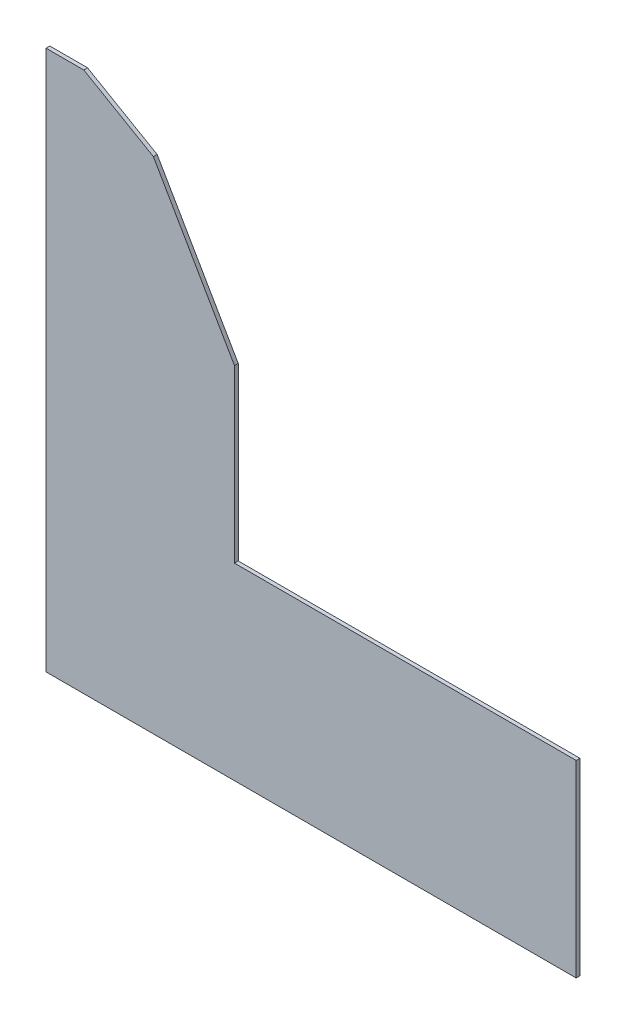
SolidWorks part; units mm, degrees
ref_plane "Front Plane" through (0, 0, 0) normal (0, 0, 1) x (1, 0, 0)
ref_plane "Top Plane" through (0, 0, 0) normal (0, 1, 0) x (1, 0, 0)
ref_plane "Right Plane" through (0, 0, 0) normal (1, 0, 0) x (0, 0, -1)
sketch "Sketch1" plane through (0, 0, 0) normal (0, 0, 1) x (1, 0, 0)
  line L0 (0, 0) -> (0, -75)
  line L3 (0, -75) -> (211, -75)
  line L6 (211, -75) -> (211, 0)
  line L7 (0, 0) -> (211, 0)
  point P3 (0, 0)
  point P4 (0, 0)
  point P8 (167.7339, 0)
  point P10 (49.7607, -70)
  point P11 (10.9259, -48.9243)
  point P12 (199.9096, -55.652)
  point P13 (177.0385, -75)
  point P14 (211, -32.8402)
  dimension "D3" = 75
  dimension "D6" = 211
extrude "Boss-Extrude1" add sketch "Sketch1" along normal blind 1.5
sketch "Sketch2" plane through (0, 0, 0) normal (0, 0, 1) x (1, 0, 0)
  line L0 (0, 0) -> (0, 140)
  line L1 (0, 140) -> (15, 140)
  line L2 (15, 140) -> (42.7128, 124)
  line L3 (42.7128, 124) -> (75, 68.077)
  line L4 (75, 68.077) -> (75, 0)
  line L5 (211, 0) -> (0, 0) construction
  line L6 (75, 0) -> (0, 0)
  point P9 (21.821, 140)
  point P10 (75, 75.8119)
  point P11 (75, 51.4444)
  point P12 (75, 62.4382)
  point P13 (75, 76.9284)
  point P14 (54.7503, 151.6912)
  dimension "D1" = 30
  dimension "D2" = 60
  dimension "D3" = 140
  dimension "D4" = 75
  dimension "D5" = 15
  dimension "D6" = 32
extrude "Boss-Extrude2" add sketch "Sketch2" along normal up to surface (1.5 mm away) up to face at (105.5, -37.5, 1.5)
